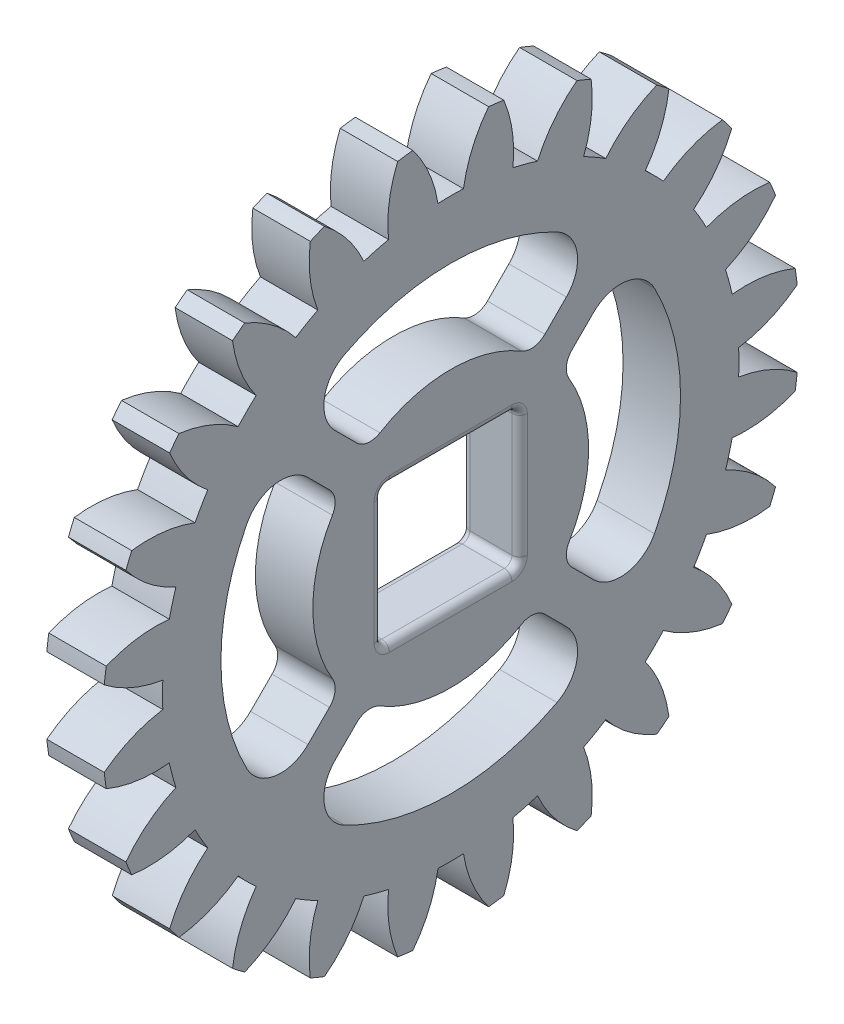
SolidWorks part; units mm, degrees
ref_plane "Plane1" through (0, 0, 0) normal (0, 0, 1) x (1, 0, 0)
ref_plane "Plane2" through (0, 0, 0) normal (0, 1, 0) x (1, 0, 0)
ref_plane "Plane3" through (0, 0, 0) normal (1, 0, 0) x (0, 0, -1)
sketch "HoldingSke" plane through (0, 0, 0) normal (0, 1, 0) x (1, 0, 0)
  line L0 (0, 0) -> (0.1305, -0.0581)
  line L1 (-15, 0) -> (100, 0) construction
  line L2 (0, 0) -> (-2.1039, 2.3779)
  line L3 (0, 0) -> (-11.863, 4.5341)
  line L4 (0, 0) -> (7.8894, 3.5126)
  line L5 (0, 0) -> (-46.8476, -17.4728)
  line L6 (0, 0) -> (-12.4344, -8.3896)
  line L7 (-2.1039, 2.3779) -> (8.6586, 51.2059)
  line L8 (-76.2, 54.61) -> (-72.9, 54.61)
  line L9 (-71.009, 38.7566) -> (-53.1078, 45.2721)
  line L10 (-76.2, 71.12) -> (104.1128, 71.12)
  line L11 (0, 0) -> (-15, 0)
  line L12 (-76.2, 101.6) -> (-75.969, 101.6)
  line L13 (24.9733, 27.94) -> (52.9518, 28.4284)
  line L14 (24.9733, 27.94) -> (24.9743, 27.94)
  line L15 (24.9733, 27.94) -> (100.4006, 29.5858)
  line L16 (-63.627, -7) -> (-12.827, -7)
  circle A0 centre (0, 0) radius 12.5
  circle A1 centre (0, 0) radius 37.5
  circle A2 centre (0, 0) radius 37.5
  circle A3 centre (0, 0) radius 12.5
  dimension "MHD" = 75
  dimension "Hub_dia" = 75
  dimension "Bore" = 25
  dimension "MBD" = 25
  dimension "Num_teeth" = 24
  dimension "Pitch" = 0.1429
  dimension "Overall_len" = 50
  dimension "Show_teeth" = 24
  dimension "Thickness" = 15
  dimension "OAL" = 50.0001
  dimension "T_dim" = 3.3
  dimension "Ap" = 20
  dimension "H" = 19.05
  dimension "Pitch_radius" = 180.3128
  dimension "Width" = 15
  dimension "Backlash" = 0.231
  dimension "Addendum_fac" = 1
  dimension "Dedendum_fac" = 1.25
  dimension "Clearance_fac" = 0.25
  dimension "Dedendum_add" = 0.001
  dimension "Module" = 7
sketch "BasProSke" plane through (0, 0, 0) normal (0, 1, 0) x (1, 0, 0)
  line L0 (-10, 0) -> (60, 0) construction
  line L1 (0, 0) -> (0, 91)
  line L2 (0, 0) -> (15, 0)
  line L3 (15, 0) -> (15, 91)
  line L4 (15, 91) -> (0, 91)
  dimension "Thickness" = 15
  dimension "Diameter" = 182
revolve "Base-Revolve" add sketch "BasProSke" angle 360 about L0
sketch "TooCutSke" plane through (0, 0, 0) normal (1, 0, 0) x (0, 0, -1)
  line L1 (0, 0) -> (0, 107) construction
  line L2 (0, 0) -> (-5.898, 83.7927) construction
  line L3 (0, 0) -> (-21.8881, 166.2567) construction
  line L4 (-5.898, 83.7927) -> (-10.9441, 83.1284) construction
  arc A0 (3.3302, 75.1753) -> (-3.3302, 75.1753) centre (0, 0) ccw
  arc A1 (9.9108, 90.4843) -> (-9.9108, 90.4843) centre (0, 0) ccw
  circle A2 centre (0, 0) radius 84 construction
  circle A3 centre (0, 0) radius 78.9342 construction
  arc A4 (-3.3302, 75.1753) -> (-9.9108, 90.4843) centre (-36.5253, 69.975) ccw
  arc A5 (9.9108, 90.4843) -> (3.3302, 75.1753) centre (36.5253, 69.975) ccw
  dimension "Root_dia" = 150.498
  dimension "Overcut_dia" = 182.0508
  dimension "Pitch_dia" = 168
  dimension "Base_dia" = 157.8684
  dimension "Flank_rad" = 33.6
  dimension "Half_ang" = 7.5
  dimension "Half_CT" = 5.0896
extrude "ToothCut" cut sketch "TooCutSke" along normal through all
fillet "Breaks" [suppressed] radius 0.14
fillet "RootFillets" [suppressed] radius 1.751
pattern_circular "TeethCuts" count 24 every 15 about axis through (-10, 0, 0) along (1, 0, 0) of "ToothCut", "RootFillets", "Breaks"
sketch "HubNeaOneSke" plane through (0, 0, 0) normal (-1, 0, 0) x (0, 0, 1)
  circle A0 centre (0, 0) radius 37.5
  dimension "Diameter" = 75
extrude "HubNearOne" [suppressed] add sketch "HubNeaOneSke" along normal blind 35.0001
sketch "HubNeaBotSke" plane through (0, 0, 0) normal (-1, 0, 0) x (0, 0, 1)
  circle A0 centre (0, 0) radius 37.5
  dimension "Diameter" = 75
extrude "HubNearBoth" [suppressed] add sketch "HubNeaBotSke" along normal blind 17.5
ref_plane "FarPln" through (15, 0, 0) normal (1, 0, 0) x (0, 0, -1)
sketch "HubFarSke" plane through (15, 0, 0) normal (1, 0, 0) x (0, 0, -1)
  circle A0 centre (0, 0) radius 37.5
  dimension "Diameter" = 75
extrude "HubFar" [suppressed] add sketch "HubFarSke" along normal blind 17.5
sketch "BorSke" plane through (0, 0, 0) normal (1, 0, 0) x (0, 0, -1)
  circle A0 centre (0, 0) radius 12.5
  dimension "Diameter" = 25
extrude "Bore" cut sketch "BorSke" along normal mid plane 100.0001
sketch "KeySke" plane through (0, 0, 0) normal (1, 0, 0) x (0, 0, -1)
  line L0 (-4, 0) -> (-4, 15.8)
  line L1 (-4, 15.8) -> (4, 15.8)
  line L2 (4, 15.8) -> (4, 0)
  line L3 (0, 0) -> (0, 34) construction
  line L4 (-4, 0) -> (4, 0)
  dimension "Offset" = 15.8
  dimension "Width" = 8
extrude "Keyway" [suppressed] cut sketch "KeySke" along normal mid plane 100.0001
pattern_circular "Keyway2" [suppressed] count 2 every 90 about axis through (-10, 0, 0) along (1, 0, 0)
sketch "Sketch1" plane through (15, 0, 0) normal (1, 0, 0) x (0, 0, -1)
  line L1 (-18, -18) -> (18, -18)
  line L2 (-18, -18) -> (-18, 18)
  line L3 (-18, 18) -> (18, 18)
  line L4 (18, -18) -> (18, 18)
  line L5 (-18, -18) -> (18, 18) construction
  line L6 (-18, 18) -> (18, -18) construction
  point P0 (0, 0)
extrude "Cut-Extrude1" cut sketch "Sketch1" against normal through all
fillet "Fillet1" radius 2 12 edges at (7.5, 18, -18) (15, 0, -18) (0, 0, -18) (7.5, -18, -18) (0, -18, 0) (15, -18, 0) (7.5, -18, 18) (0, 0, 18) (15, 0, 18) (0, 18, 0) (15, 18, 0) (7.5, 18, 18)
sketch "Sketch2" plane through (15, 0, 0) normal (1, 0, 0) x (0, 0, -1)
  line L0 (-42.4264, -42.4264) -> (-25.4558, -25.4558)
  line L1 (42.4264, -42.4264) -> (-42.4264, -42.4264)
  line L2 (42.4264, -42.4264) -> (42.4264, 42.4264)
  line L3 (42.4264, 42.4264) -> (-42.4264, 42.4264)
  line L4 (-42.4264, -42.4264) -> (-42.4264, 42.4264)
  line L5 (42.4264, -42.4264) -> (-42.4264, 42.4264) construction
  line L6 (42.4264, 42.4264) -> (-42.4264, -42.4264) construction
  line L7 (-42.4264, 42.4264) -> (-25.4558, 25.4558)
  line L8 (42.4264, 42.4264) -> (25.4558, 25.4558)
  line L9 (42.4264, -42.4264) -> (25.4558, -25.4558)
  line L10 (0, 93.5134) -> (0, -131.7985) construction
  line L11 (-101.6499, 0) -> (107.2515, 0) construction
  line L12 (-69.8214, 62.7503) -> (64.2571, -71.3282)
  line L13 (-68.7479, 75.819) -> (65.3306, -58.2595)
  line L14 (-94.7628, -101.8339) -> (104.589, 97.5179)
  line L15 (-112.3465, -105.2754) -> (72.5804, 79.6515)
  circle A0 centre (0, 0) radius 60
  circle A1 centre (0, 0) radius 36
  dimension "D1" = 5
  dimension "D2" = 5
  dimension "D3" = 5
  dimension "D4" = 5
extrude "Cut-Extrude2" cut sketch "Sketch2" against normal through all contours L15 A0 L13 L3 | A1 L15 L3 L13 | L13 A0 L14 L2 | A1 L13 L2 L14 | L14 A0 L12 L1 | A1 L14 L1 L12 | L12 A0 L15 L4 | A1 L12 L4 L15
fillet "Fillet2" radius 5 8 edges at (7.5, -28.7447, -21.6736) (7.5, 21.6736, 28.7447) (7.5, -21.6736, 28.7447) (7.5, 28.7447, -21.6736) (7.5, -28.7447, 21.6736) (7.5, 21.6736, -28.7447) (7.5, -21.6736, -28.7447) (7.5, 28.7447, 21.6736)
fillet "Fillet3" radius 10 8 edges at (7.5, -45.8144, 38.7433) (7.5, 38.7433, -45.8144) (7.5, -38.7433, -45.8144) (7.5, 45.8144, 38.7433) (7.5, -45.8144, -38.7433) (7.5, 38.7433, 45.8144) (7.5, -38.7433, 45.8144) (7.5, 45.8144, -38.7433)
equation "' \"Module@HoldingSke\" = 6.35"
equation "' \"Num_teeth@HoldingSke\" = 12"
equation "' \"Ap@HoldingSke\" =  20"
equation "' \"Ap@HoldingSke\" = 20"
equation "' \"Width@HoldingSke\" = 0.5 * 25.4"
equation "' \"Hub_dia@HoldingSke\"= 1 * 25.4"
equation "' \"Hub_dia@HoldingSke\" = 1 * 25.4"
equation "' \"Overall_len@HoldingSke\" = 1.0 * 25.4"
equation "' \"Bore@HoldingSke\" = 0.75 * 25.4"
equation "' \"T_dim@HoldingSke\" = 0.1 * 25.4"
equation "' \"Width@KeySke\" = 0.25 * 25.4"
equation "' \"Show_teeth@HoldingSke\" = 13"
equation "' \"Backlash@HoldingSke\" = 0.009 * 25.4"
equation "' \"Addendum_fac@HoldingSke\" = 1.0"
equation "' \"Dedendum_fac@HoldingSke\" = 1.25"
equation "' \"Dedendum_add@HoldingSke\" = 0.00005 * 25.4"
equation "' \"Clearance_fac@HoldingSke\" = 0.25"
equation "\"Pitch@HoldingSke\" = 1 / \"Module@HoldingSke\""
equation "\"Overcut_dia@TooCutSke\" = (\"Num_teeth@HoldingSke\" + 2 * \"Addendum_fac@HoldingSke\") / \"Pitch@HoldingSke\" + 0.002 * 25.4"
equation "\"Pitch_dia@TooCutSke\" = \"Num_teeth@HoldingSke\" / \"Pitch@HoldingSke\""
equation "\"Base_dia@TooCutSke\" = \"Num_teeth@HoldingSke\" / \"Pitch@HoldingSke\" * cos((\"Ap@HoldingSke\"  * 3.14159265 / 180))"
equation "\"Root_dia@TooCutSke\" = (\"Num_teeth@HoldingSke\" + 2) / \"Pitch@HoldingSke\" - 2 * (\"Addendum_fac@HoldingSke\" + \"Dedendum_fac@HoldingSke\") / \"Pitch@HoldingSke\" - \"Dedendum_add@HoldingSke\" * 2"
equation "\"Half_ang@TooCutSke\" = 180 / \"Num_teeth@HoldingSke\""
equation "\"Half_CT@TooCutSke\" = \"Num_teeth@HoldingSke\" / \"Pitch@HoldingSke\" * sin((3.14159265 / 2 / \"Num_teeth@HoldingSke\")) / 2 - 7 * \"Backlash@HoldingSke\" / 4"
equation "\"Flank_rad@TooCutSke\" = \"Num_teeth@HoldingSke\" / \"Pitch@HoldingSke\" / 5"
equation "\"Radius@RootFillets\" = \"Clearance_fac@HoldingSke\" / \"Pitch@HoldingSke\" + \"Dedendum_add@HoldingSke\""
equation "\"Break_rad@Breaks\" = 0.02 / \"Pitch@HoldingSke\""
equation "\"Thickness@HoldingSke\" = \"Width@HoldingSke\""
equation "\"OAL@HoldingSke\" = \"Thickness@HoldingSke\""
equation "\"MHD@HoldingSke\" = (\"Num_teeth@HoldingSke\" + 2) / \"Pitch@HoldingSke\" - 2 * (\"Addendum_fac@HoldingSke\" + \"Dedendum_fac@HoldingSke\")  / \"Pitch@HoldingSke\" - \"Dedendum_add@HoldingSke\" * 2"
equation "\"MBD@HoldingSke\" = (\"Num_teeth@HoldingSke\" + 2) / \"Pitch@HoldingSke\" - 2 * (\"Addendum_fac@HoldingSke\" + \"Dedendum_fac@HoldingSke\")  / \"Pitch@HoldingSke\" - \"Dedendum_add@HoldingSke\" * 2 - 0.002 * 25.4"
equation "\"MHD@HoldingSke\" = ((sgn( \"MHD@HoldingSke\" - \"Hub_dia@HoldingSke\" )-1)*( \"MHD@HoldingSke\" - \"Hub_dia@HoldingSke\" ))/-2+ \"Hub_dia@HoldingSke\""
equation "\"MBD@HoldingSke\" = ((sgn( \"MBD@HoldingSke\" - \"Bore@HoldingSke\" )-1)*( \"MBD@HoldingSke\" - \"Bore@HoldingSke\" ))/-2+ \"Bore@HoldingSke\""
equation "\"OAL@HoldingSke\" = ((sgn( \"OAL@HoldingSke\" - \"Overall_len@HoldingSke\" )+1)*( \"OAL@HoldingSke\" - \"Overall_len@HoldingSke\" ))/2 + \"Overall_len@HoldingSke\" + 0.000002 * 25.4"
equation "\"Num_teeth@TeethCuts\" = int( \"Show_teeth@HoldingSke\" ) + 1"
equation "\"Num_teeth@TeethCuts\" = ((sgn( \"Num_teeth@TeethCuts\" - \"Num_teeth@HoldingSke\" )-1)*( \"Num_teeth@TeethCuts\" - \"Num_teeth@HoldingSke\" ))/-2+ \"Num_teeth@HoldingSke\""
equation "\"Num_teeth@TeethCuts\" = ((sgn( \"Num_teeth@TeethCuts\" - 2.0)+1)*( \"Num_teeth@TeethCuts\" - 2.0))/2 +2.0"
equation "\"Angle@TeethCuts\" = 360.0 / \"Num_teeth@HoldingSke\""
equation "\"Diameter@BasProSke\" = (\"Num_teeth@HoldingSke\" + 2 * \"Addendum_fac@HoldingSke\") / \"Pitch@HoldingSke\""
equation "\"Thickness@BasProSke\"  = \"Thickness@HoldingSke\""
equation "' \"Fillet_rad@BasProSke\" =  \"Thickness@HoldingSke\" * 0.05"
equation "' \"Fillet_rad@BasProSke\" = \"Thickness@HoldingSke\" * 0.05"
equation "\"MHD@HoldingSke\" = ((sgn( \"MHD@HoldingSke\" - \"Root_dia@TooCutSke\" )-1)*( \"MHD@HoldingSke\" - \"Root_dia@TooCutSke\" ))/-2+ \"Root_dia@TooCutSke\""
equation "\"Diameter@HubNeaOneSke\" = \"MHD@HoldingSke\""
equation "\"Length@HubNearOne\" = \"OAL@HoldingSke\" - \"Thickness@BasProSke\""
equation "\"Diameter@HubNeaBotSke\" = \"MHD@HoldingSke\""
equation "\"Length@HubNearBoth\" = ( \"OAL@HoldingSke\" - \"Thickness@BasProSke\" ) / 2.0"
equation "\"Thickness@FarPln\" = \"Thickness@BasProSke\""
equation "\"Diameter@HubFarSke\" = \"MHD@HoldingSke\""
equation "\"Length@HubFar\" = ( \"OAL@HoldingSke\" - \"Thickness@BasProSke\" ) / 2.0"
equation "\"Diameter@BorSke\" = \"MBD@HoldingSke\""
equation "\"D1@Bore\" = \"OAL@HoldingSke\" * 2.0"
equation "\"D1@Keyway\" = \"OAL@HoldingSke\" * 2.0"
equation "\"Offset@KeySke\" = \"T_dim@HoldingSke\" + \"MBD@HoldingSke\" / 2.0"
